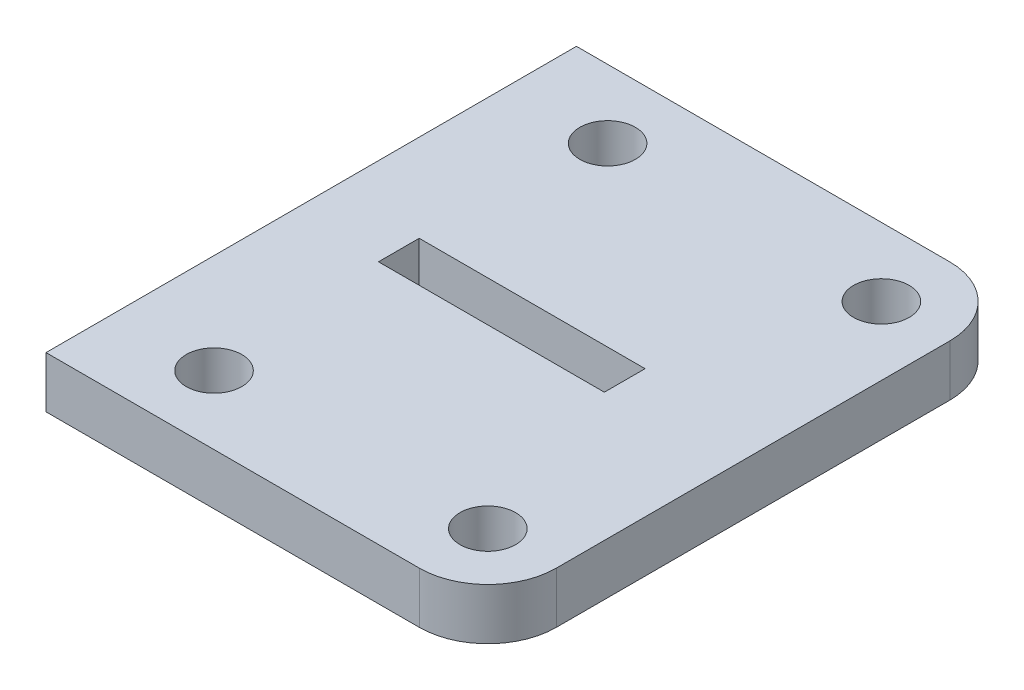
SolidWorks part; units mm, degrees
material "AISI 1020"
ref_plane "Plano frontal" through (0, 0, 0) normal (0, 0, 1) x (1, 0, 0)
ref_plane "Plano superior" through (0, 0, 0) normal (0, 1, 0) x (1, 0, 0)
ref_plane "Plano direito" through (0, 0, 0) normal (1, 0, 0) x (0, 0, -1)
sketch "Esboço1" plane through (0, 0, 0) normal (0, 0, 1) x (1, 0, 0)
  line L0 (0, 0) -> (0, 100)
  line L1 (0, 100) -> (60, 0)
  line L2 (60, 0) -> (0, 0)
  dimension "D1" = 100
  dimension "D2" = 60
extrude "Ressalto-extrusão1" add sketch "Esboço1" along normal blind 30
ref_plane "Plano1" through (6, 0, 0) normal (-1, 0, 0) x (0, 0, 1)
sketch "Esboço2" plane through (6, 0, 0) normal (-1, 0, 0) x (0, 0, 1)
  line L0 (30, 100) -> (0, 100) construction
  line L1 (18, 100) -> (30, 100)
  line L2 (18, 100) -> (18, 6)
  line L3 (18, 6) -> (30, 6)
  line L4 (30, 100) -> (30, 6)
  line L5 (0, 0) -> (0, 100) construction
  line L6 (12, 100) -> (0, 100)
  line L7 (12, 100) -> (12, 6)
  line L8 (12, 6) -> (0, 6)
  line L9 (0, 100) -> (0, 6)
  line L10 (30, 0) -> (0, 0) construction
  line L11 (30, 0) -> (30, 100) construction
  line L12 (18, 6) -> (12, 6) construction
  line L13 (15, 6) -> (15, 0) construction
  dimension "D1" = 6
  dimension "D2" = 6
extrude "Corte-extrusão1" cut sketch "Esboço2" against normal through all
sketch "Esboço3" plane through (6, 0, 0) normal (1, 0, 0) x (0, 0, -1)
  line L1 (-30, 90) -> (0, 90)
  line L2 (-30, 90) -> (-30, 100)
  line L3 (-30, 100) -> (0, 100)
  line L4 (0, 90) -> (0, 100)
extrude "Corte-extrusão2" cut sketch "Esboço3" against normal through all
sketch "Esboço4" plane through (0, 6, 0) normal (0, 1, 0) x (1, 0, 0)
  line L1 (56.4, 0) -> (60, 0)
  line L2 (56.4, 0) -> (56.4, -30)
  line L3 (56.4, -30) -> (60, -30)
  line L4 (60, 0) -> (60, -30)
extrude "Corte-extrusão3" cut sketch "Esboço4" against normal through all
sketch "Esboço5" plane through (0, 0, 30) normal (0, 0, 1) x (1, 0, 0)
  line L1 (56.4, 6) -> (0, 6)
  line L2 (56.4, 6) -> (56.4, 0)
  line L3 (56.4, 0) -> (0, 0)
  line L4 (0, 6) -> (0, 0)
extrude "Ressalto-extrusão2" add sketch "Esboço5" along normal blind 16
sketch "Esboço6" plane through (0, 0, 0) normal (0, 0, -1) x (-1, 0, 0)
  line L1 (-56.4, 6) -> (0, 6)
  line L2 (-56.4, 6) -> (-56.4, 0)
  line L3 (-56.4, 0) -> (0, 0)
  line L4 (0, 6) -> (0, 0)
extrude "Ressalto-extrusão3" add sketch "Esboço6" along normal blind 16
fillet "Filete1" radius 8 2 edges at (3, 6, 30) (3, 6, 0)
fillet "Filete2" radius 8 2 edges at (56.4, 3, -16) (56.4, 3, 46)
fillet "Filete3" radius 8 2 edges at (3, 90, 30) (3, 90, 0)
fillet "Filete4" radius 4 2 edges at (31.2, 6, 18) (31.2, 6, 12)
sketch "Esboço7" plane through (6, 0, 0) normal (1, 0, 0) x (0, 0, -1)
  line L0 (-15, 90) -> (-15, 0) construction
  line L1 (-18, 90) -> (-12, 90) construction
  line L2 (8, 0) -> (-38, 0) construction
  line L3 (-22, 90) -> (-18, 90) construction
  circle A0 centre (-23, 78) radius 3.175
  circle A1 centre (-23, 48) radius 3.175
  circle A2 centre (-23, 18) radius 3.175
  circle A3 centre (-7, 18) radius 3.175
  circle A4 centre (-7, 48) radius 3.175
  circle A5 centre (-7, 78) radius 3.175
  dimension "D1" = 30
  dimension "D2" = 30
  dimension "D4" = 6.35
  dimension "D5" = 12
  dimension "D3" = 8
extrude "Corte-extrusão4" cut sketch "Esboço7" against normal through all
sketch "Esboço8" plane through (0, 6, 0) normal (0, 1, 0) x (1, 0, 0)
  line L0 (48.4, -15) -> (56.4, -15) construction
  line L1 (16.4, 8) -> (48.4, 8) construction
  line L2 (16.4, 8) -> (16.4, -38) construction
  line L3 (16.4, -38) -> (48.4, -38) construction
  line L4 (48.4, 8) -> (48.4, -38) construction
  line L5 (56.4, -8) -> (56.4, -22) construction
  circle A0 centre (48.4, 8) radius 3.25
  circle A1 centre (48.4, -38) radius 3.25
  circle A2 centre (16.4, -38) radius 3.25
  circle A3 centre (16.4, 8) radius 3.25
  dimension "D4" = 6.5
  dimension "D1" = 8
  dimension "D2" = 32
  dimension "D3" = 46
extrude "Corte-extrusão5" cut sketch "Esboço8" against normal through all
sketch "Esboço9" plane through (0, 6, 0) normal (0, 1, 0) x (1, 0, 0)
  line L0 (56.4, -22) -> (56.4, -38) construction
  line L1 (0, 16) -> (56.4, 16)
  line L2 (0, 16) -> (0, -46)
  line L3 (0, -46) -> (56.4, -46)
  line L4 (56.4, 16) -> (56.4, -46)
  line L5 (48.4, -46) -> (0, -46) construction
extrude "Corte-extrusão6" cut sketch "Esboço9" along normal through all
sketch "Esboço10" plane through (0, 6, 0) normal (0, 1, 0) x (1, 0, 0)
  line L0 (0, -46) -> (0, 16) construction
  line L1 (0, -12.62) -> (56.4, -12.62) construction
  line L2 (0, -12.62) -> (0, -17.38) construction
  line L3 (0, -17.38) -> (56.4, -17.38) construction
  line L4 (56.4, -12.62) -> (56.4, -17.38) construction
  line L5 (56.4, 8) -> (56.4, -38) construction
  line L6 (0, 16) -> (0, -12.62) construction
  line L7 (0, -17.38) -> (0, -46) construction
  line L9 (15, -12.62) -> (41.4, -12.62)
  line L10 (15, -12.62) -> (15, -17.38)
  line L11 (15, -17.38) -> (41.4, -17.38)
  line L12 (41.4, -12.62) -> (41.4, -17.38)
  dimension "D1" = 4.76
  dimension "D2" = 15
  dimension "D3" = 15
extrude "Corte-extrusão7" cut sketch "Esboço10" against normal through all
sketch "Esboço11" plane through (0, 6, 0) normal (0, 1, 0) x (1, 0, 0)
  line L0 (0, 16) -> (48.4, 16) construction
  line L1 (4.76, 16) -> (0, 16)
  line L2 (4.76, 16) -> (4.76, -46)
  line L3 (4.76, -46) -> (0, -46)
  line L4 (0, 16) -> (0, -46)
  dimension "D1" = 4.76
extrude "Corte-extrusão8" cut sketch "Esboço11" against normal through all
